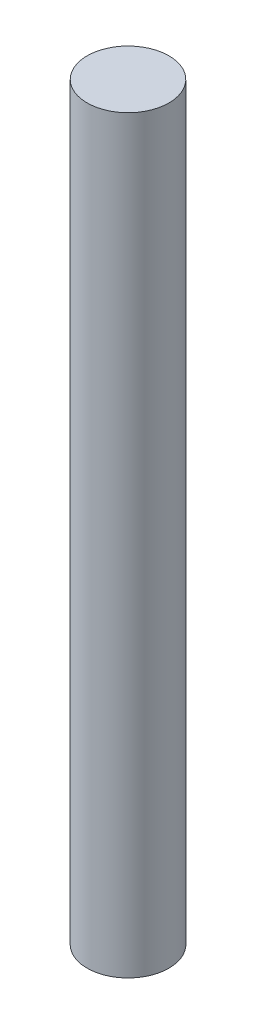
SolidWorks part; units mm, degrees
ref_plane "Front Plane" through (0, 0, 0) normal (0, 0, 1) x (1, 0, 0)
ref_plane "Top Plane" through (0, 0, 0) normal (0, 1, 0) x (1, 0, 0)
ref_plane "Right Plane" through (0, 0, 0) normal (1, 0, 0) x (0, 0, -1)
sketch "Sketch1" plane through (0, 0, 0) normal (0, 0, 1) x (1, 0, 0)
  line L0 (0, 0) -> (-3, 0)
  line L1 (-3, 0) -> (-3, -27)
  line L2 (-3, -27) -> (-3, -28.2718)
  line L3 (-3, -28.2718) -> (-3, -55)
  line L4 (-3, -55) -> (0, -55)
  line L5 (0, -55) -> (0, 0) construction
  line L6 (0, 0) -> (0, -55)
  dimension "D1" = 6
  dimension "D2" = 55
  dimension "D3" = 6
  dimension "D4" = 28
revolve "Revolve1" add sketch "Sketch1" angle 360 about L5
